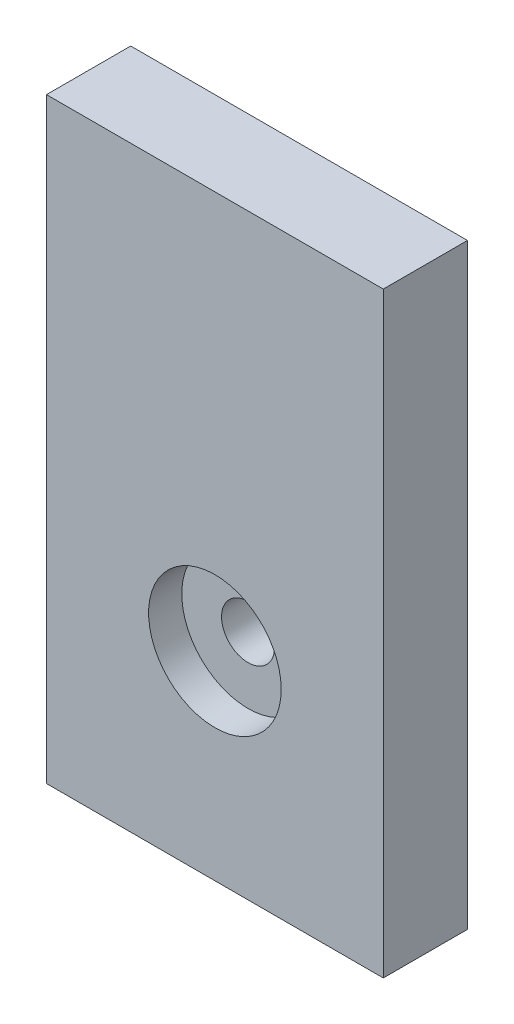
SolidWorks part; units mm, degrees
material "Aleación 1060"
ref_plane "Alzado" through (0, 0, 0) normal (0, 0, 1) x (1, 0, 0)
ref_plane "Planta" through (0, 0, 0) normal (0, 1, 0) x (1, 0, 0)
ref_plane "Vista lateral" through (0, 0, 0) normal (1, 0, 0) x (0, 0, -1)
sketch "Croquis1" plane through (0, 0, 0) normal (0, 0, 1) x (1, 0, 0)
  line L1 (25.4, -40) -> (-25.4, -40)
  line L2 (25.4, -40) -> (25.4, 40)
  line L3 (25.4, 40) -> (-25.4, 40)
  line L4 (-25.4, -40) -> (-25.4, 40)
  line L5 (25.4, -40) -> (-25.4, 40) construction
  line L6 (25.4, 40) -> (-25.4, -40) construction
  circle A0 centre (0, -20) radius 4
  point P0 (0, 0)
  dimension "D3" = 8
  dimension "D1" = 50.8
  dimension "D2" = 80
  dimension "D4" = 20
extrude "Saliente-Extruir1" add sketch "Croquis1" along normal blind 12.7
sketch "Croquis2" plane through (0, 0, 12.7) normal (0, 0, 1) x (1, 0, 0)
  circle A0 centre (0, -20) radius 10
  dimension "D1" = 20
extrude "Cortar-Extruir1" cut sketch "Croquis2" against normal blind 5
sketch "Croquis3" plane through (0, -40, 0) normal (0, -1, 0) x (1, 0, 0)
  line L4 (-25.4, 0) -> (25.4, 0)
  line L5 (25.4, 0) -> (25.4, 12.7)
  line L6 (25.4, 12.7) -> (-25.4, 12.7)
  line L7 (-25.4, 12.7) -> (-25.4, 0)
  line L8 (-25.4, 0) -> (25.4, 0)
  line L9 (25.4, 0) -> (25.4, 12.7)
  line L10 (25.4, 12.7) -> (-25.4, 12.7)
  line L11 (-25.4, 12.7) -> (-25.4, 0)
  dimension "D1" = 0
extrude "Saliente-Extruir2" add sketch "Croquis3" along normal blind 10
